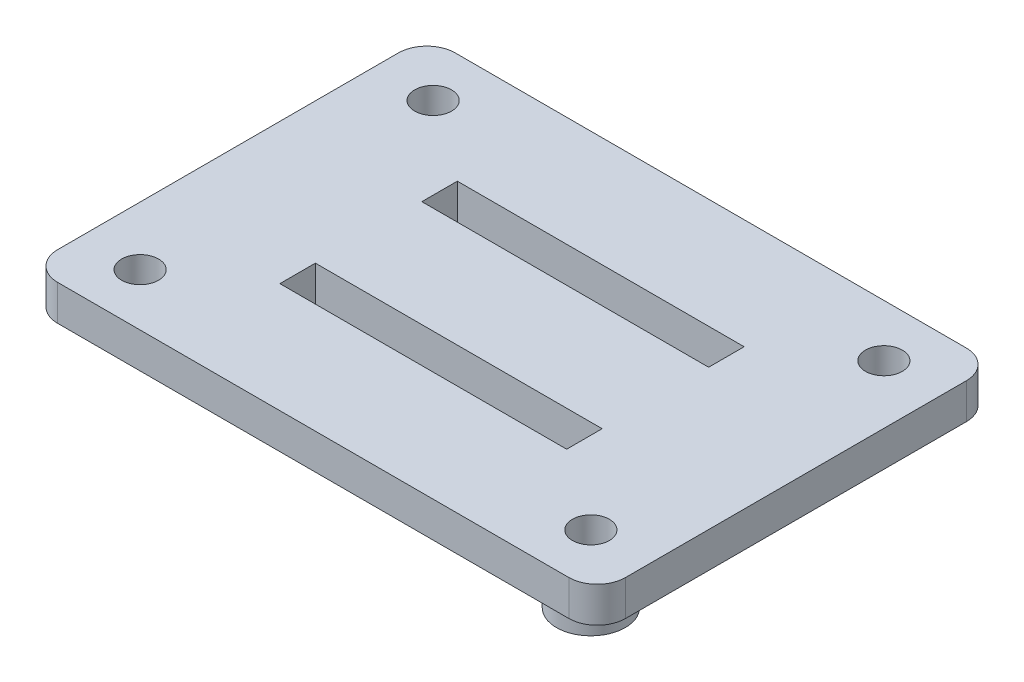
SolidWorks part; units mm, degrees
other "标注1"
sketch "草图8" plane through (-40, 4.6, -28) normal (0, 1, 0) x (1, 0, 0)
ref_plane "前视基准面" through (0, 0, 0) normal (0, 0, 1) x (1, 0, 0)
ref_plane "上视基准面" through (0, 0, 0) normal (0, 1, 0) x (1, 0, 0)
ref_plane "右视基准面" through (0, 0, 0) normal (1, 0, 0) x (0, 0, -1)
other "Configuration Table"
sketch "草图1" plane through (0, 0, 0) normal (0, 1, 0) x (1, 0, 0)
  line L0 (-89.3251, 0) -> (102.0425, 0) construction
  line L1 (0, 56.7239) -> (0, -62.578) construction
  line L2 (-20.2, -7.5) -> (20.2, -7.5)
  line L3 (-20.2, 12.5) -> (20.2, 12.5)
  line L4 (-20.2, 12.5) -> (-20.2, 7.5)
  line L5 (-20.2, 7.5) -> (20.2, 7.5)
  line L6 (20.2, 12.5) -> (20.2, 7.5)
  line L7 (-20.2, 12.5) -> (20.2, 7.5) construction
  line L8 (-20.2, 7.5) -> (20.2, 12.5) construction
  line L9 (20.2, -12.5) -> (20.2, -7.5)
  line L10 (-20.2, -12.5) -> (20.2, -12.5)
  line L11 (-20.2, -12.5) -> (-20.2, -7.5)
  circle A0 centre (-31.75, 20.6375) radius 2.6
  circle A4 centre (31.75, 20.6375) radius 2.6
  circle A5 centre (31.75, -20.6375) radius 2.6
  circle A6 centre (-31.75, -20.6375) radius 2.6
  point P13 (0, 10)
  dimension "D5" = 5.2
  dimension "D9" = 5.2
  dimension "D7" = 10
  dimension "D1" = 40.4
  dimension "D2" = 31.75
  dimension "D3" = 5
  dimension "D4" = 20.6375
  dimension "D8" = 5
  dimension "D10" = 40.4
  dimension "D11" = 8.1375
  dimension "D12" = 31.75
sketch "草图3" plane through (0, 0, 0) normal (0, 1, 0) x (1, 0, 0)
  line L1 (-40, -28) -> (40, -28)
  line L2 (-40, -28) -> (-40, 28)
  line L3 (-40, 28) -> (40, 28)
  line L4 (40, -28) -> (40, 28)
  line L5 (-40, -28) -> (40, 28) construction
  line L6 (-40, 28) -> (40, -28) construction
  point P0 (0, 0)
  dimension "D1" = 56
  dimension "D2" = 80
extrude "凸台-拉伸1" add sketch "草图3" along normal blind 5
extrude "切除-拉伸1" cut sketch "草图1" along normal up to surface (5 mm away) up to face at (0, 5, 0)
sketch "草图5" plane through (0, 0, 0) normal (0, -1, 0) x (1, 0, 0)
  circle A0 centre (31.75, 20.6375) radius 4.85
  dimension "D1" = 9.7
extrude "凸台-拉伸2" add sketch "草图5" along normal blind 4.5
sketch "草图7" plane through (0, 5, 0) normal (0, 1, 0) x (1, 0, 0)
  line L0 (40, -28) -> (40, 28) construction
  line L1 (31.75, 20.6375) -> (50, 20.6375)
  line L2 (31.75, 20.6375) -> (31.75, -28.0079)
  line L3 (31.75, -28.0079) -> (50, -28.0079)
  line L4 (50, 20.6375) -> (50, -28.0079)
  dimension "D1" = 10
fillet "圆角2" radius 4 4 edges at (-40, 2.5, -28) (40, 2.5, -28) (40, 2.5, 28) (-40, 2.5, 28)
